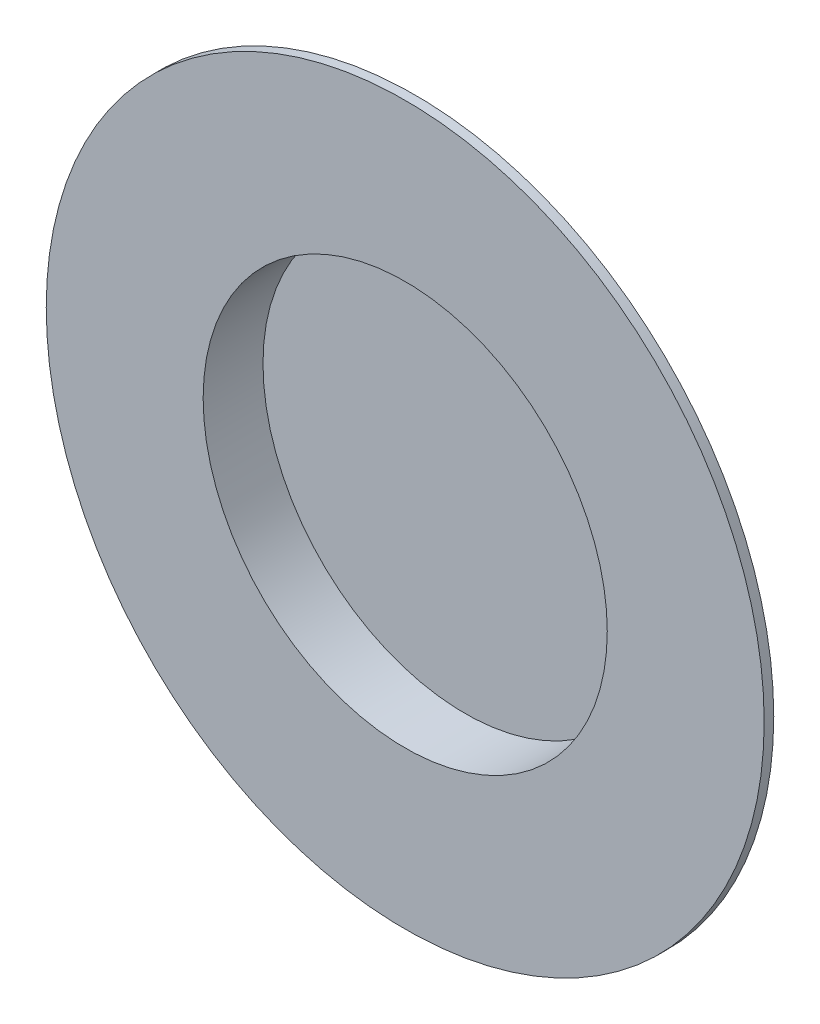
SolidWorks part; units mm, degrees
ref_plane "Front Plane" through (0, 0, 0) normal (0, 0, 1) x (1, 0, 0)
ref_plane "Top Plane" through (0, 0, 0) normal (0, 1, 0) x (1, 0, 0)
ref_plane "Right Plane" through (0, 0, 0) normal (1, 0, 0) x (0, 0, -1)
sketch "Sketch1" plane through (0, 0, 0) normal (0, 0, 1) x (1, 0, 0)
  circle A0 centre (-74.4149, -31.3834) radius 113.3367
extrude "Boss-Extrude1" add sketch "Sketch1" along normal blind 2
sketch "Sketch3" plane through (0, 0, 2) normal (0, 0, 1) x (1, 0, 0)
  circle A0 centre (-74.4149, -31.3834) radius 113.3367
extrude "Boss-Extrude2" add sketch "Sketch3" along normal blind 33 draft 66 draft outward yes
sketch "Sketch4" plane through (0, 0, 35) normal (0, 0, 1) x (1, 0, 0)
  circle A1 centre (-74.4149, -31.3834) radius 187.4559
  circle A2 centre (-74.4149, -31.3834) radius 187.4559
  dimension "D1" = 0
extrude "Boss-Extrude3" add sketch "Sketch4" along normal blind 5
sketch "Sketch5" plane through (0, 0, 0) normal (0, 0, -1) x (-1, 0, 0)
  line L0 (187.7515, -31.3834) -> (-38.9218, -31.3834)
  circle A0 centre (74.4149, -31.3834) radius 113.3367 construction
ref_plane "Plane1" through (0, -31.3834, 0) normal (0, -1, 0) x (-1, 0, 0)
sketch "Sketch6" plane through (0, -31.3834, 0) normal (0, -1, 0) x (-1, 0, 0)
  line L0 (74.4149, 21.1086) -> (74.4149, 76.3568)
  line L2 (74.4149, -8.7552) -> (-31.1041, -8.7552)
  line L3 (74.4149, -8.7552) -> (74.4149, -57.0351)
  line L4 (74.4149, -57.0351) -> (-31.1041, -57.0351)
  line L5 (-31.1041, -8.7552) -> (-31.1041, -57.0351)
revolve "Cut-Revolve1" cut sketch "Sketch6" angle 360 about L0
sketch "Sketch7" plane through (0, 0, 0) normal (0, 0, -1) x (-1, 0, 0)
  circle A0 centre (-74.3001, -31.3834) radius 25
  circle A1 centre (74.4149, -180.0984) radius 25
  circle A2 centre (74.4149, 117.3316) radius 25
  circle A3 centre (223.1298, -31.3834) radius 25
  point P11 (74.4149, -31.3834)
  dimension "D1" = 50
  dimension "D2" = 4
extrude "Cut-Extrude1" cut sketch "Sketch7" against normal blind 30.5522
